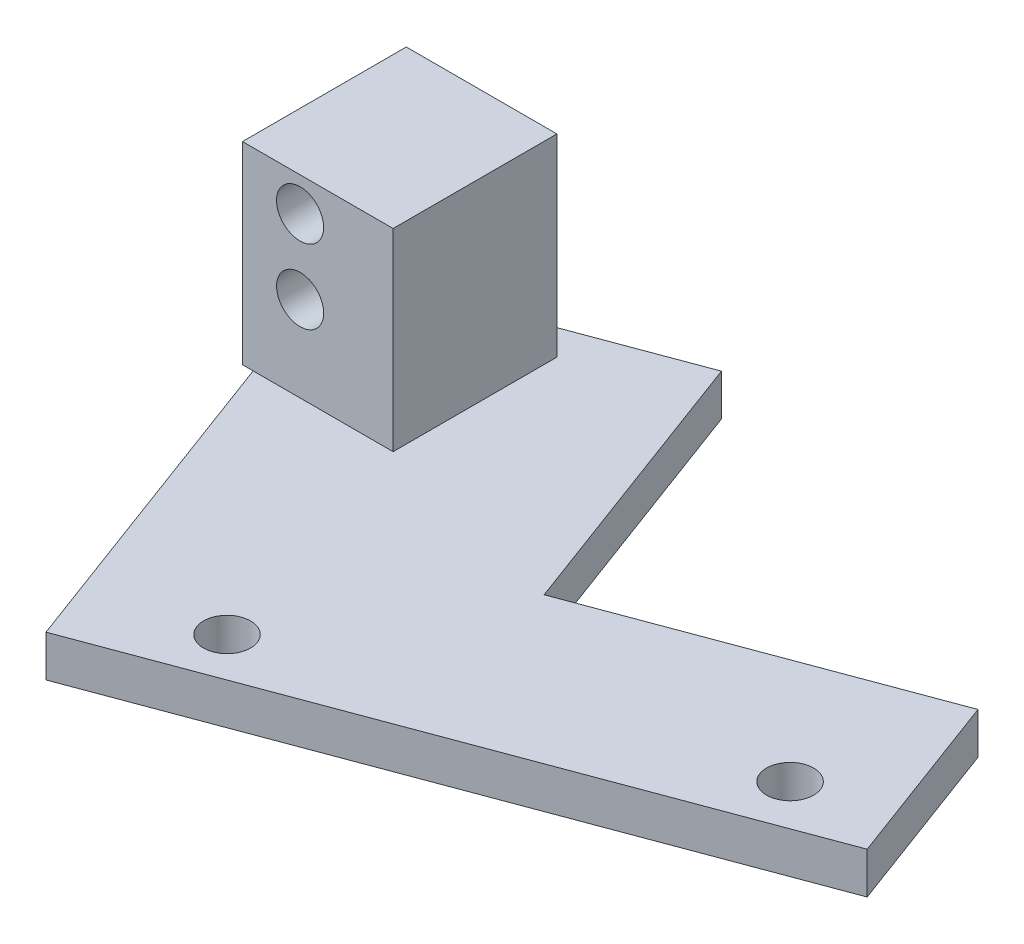
SolidWorks part; units mm, degrees
ref_plane "Front Plane" through (0, 0, 0) normal (0, 0, 1) x (1, 0, 0)
ref_plane "Top Plane" through (0, 0, 0) normal (0, 1, 0) x (1, 0, 0)
ref_plane "Right Plane" through (0, 0, 0) normal (1, 0, 0) x (0, 0, -1)
sketch "Sketch1" plane through (0, 0, 0) normal (0, 0, 1) x (1, 0, 0)
  line L0 (-111.8199, 128.5717) -> (-91.4999, 128.5717)
  line L1 (-122.8766, 128.5659) -> (-97.86, 128.5791) construction
  line L2 (-91.4999, 128.5717) -> (-91.4999, 102.49)
  line L3 (-91.4999, 102.49) -> (-111.8199, 102.49)
  line L4 (-111.8199, 102.49) -> (-111.8199, 128.5717)
  circle A0 centre (-104.0505, 124) radius 3.175
  circle A1 centre (-104.0452, 114) radius 3.175
  dimension "D4" = 6.35
  dimension "D5" = 6.35
  dimension "D1" = 20.32
  dimension "D2" = 6.35
  dimension "D3" = 3.81
extrude "Boss-Extrude1" add sketch "Sketch1" along normal up to surface (22.098 mm away)
ref_plane "Plane1" through (0, 102.49, 0) normal (0, 1, 0) x (1, 0, 0)
sketch "Sketch2" plane through (0, 102.49, 0) normal (0, 1, 0) x (1, 0, 0)
  line L4 (-91.4999, -22.098) -> (-111.8199, -22.098) construction
  line L6 (-93.8327, -66.5977) -> (-13.0724, -36.5641)
  line L9 (-116.8518, -4.6994) -> (-93.8327, -66.5977)
  line L10 (-116.8518, -4.6994) -> (-78.7605, 9.4662)
  line L11 (-78.7605, 9.4662) -> (-64.5949, -28.6251)
  line L12 (-64.5949, -28.6251) -> (-21.9259, -12.757)
  line L13 (-21.9259, -12.757) -> (-13.0724, -36.5641)
  circle A0 centre (-81.3473, -54.66) radius 3.175
  circle A1 centre (-26.1725, -33.8627) radius 3.175
  circle A2 centre (-81.3473, -54.66) radius 3.175 construction
  circle A3 centre (-26.1725, -33.8627) radius 3.175 construction
  dimension "D5" = 15.24
  dimension "D9" = 6.35
  dimension "D10" = 6.35
  dimension "D2" = 25.4
  dimension "D3" = 66.04
  dimension "D4" = 40.64
  dimension "D6" = 40.8958
  dimension "D7" = 86.164
  dimension "D8" = 69.601
extrude "Boss-Extrude2" add sketch "Sketch2" against normal blind 5.588
